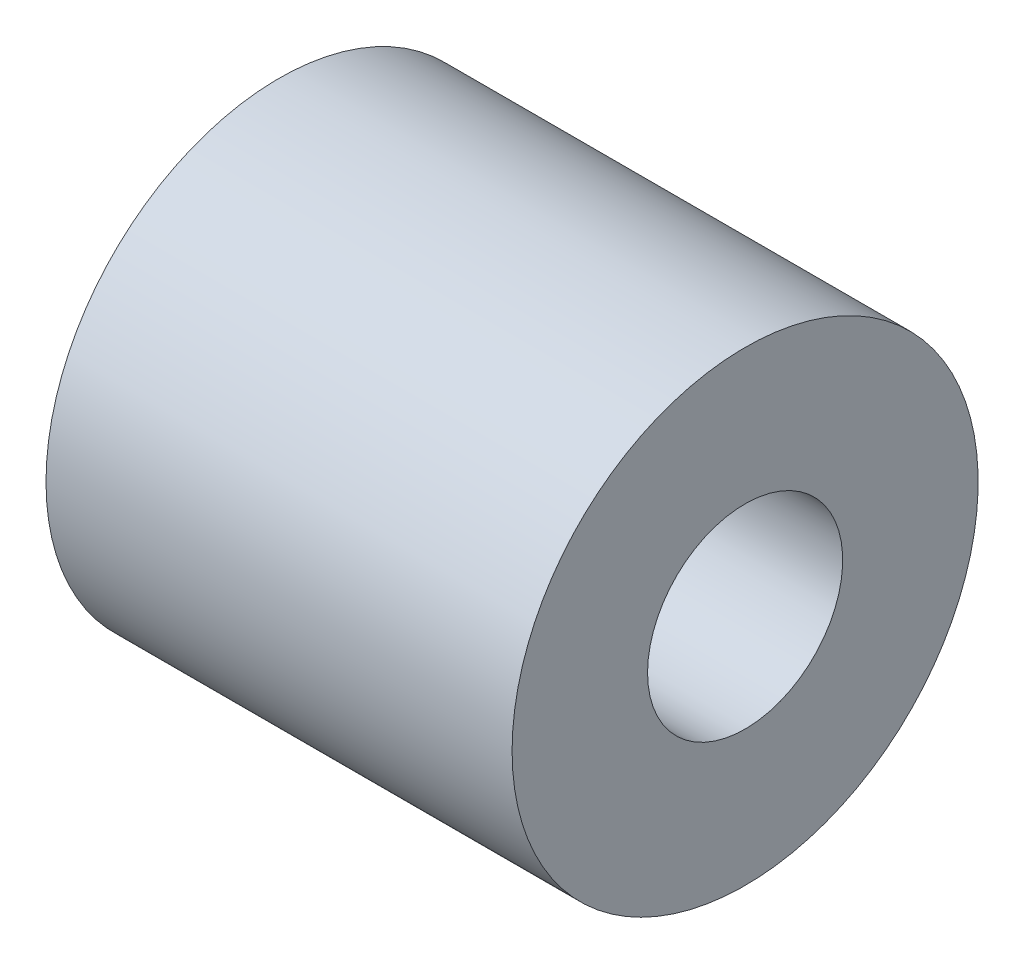
SolidWorks part; units mm, degrees
material "Nylon 101"
ref_plane "Front Plane" through (0, 0, 0) normal (0, 0, 1) x (1, 0, 0)
ref_plane "Top Plane" through (0, 0, 0) normal (0, 1, 0) x (1, 0, 0)
ref_plane "Right Plane" through (0, 0, 0) normal (1, 0, 0) x (0, 0, -1)
sketch "Sketch1" plane through (0, 0, 0) normal (1, 0, 0) x (0, 0, -1)
  circle A0 centre (0, 0) radius 4.7625
  circle A1 centre (0, 0) radius 1.9939
  dimension "D1" = 9.525
  dimension "D2" = 3.9878
extrude "Boss-Extrude1" add sketch "Sketch1" along normal mid plane 9.525
